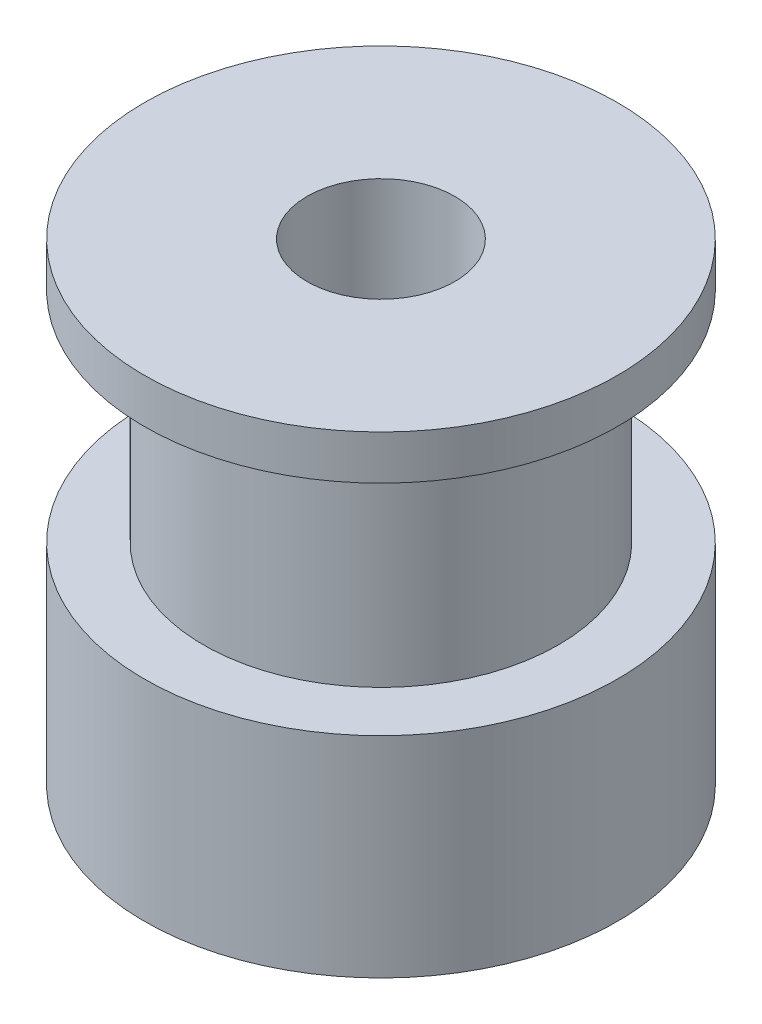
SolidWorks part; units mm, degrees
ref_plane "前视基准面" through (0, 0, 0) normal (0, 0, 1) x (1, 0, 0)
ref_plane "上视基准面" through (0, 0, 0) normal (0, 1, 0) x (1, 0, 0)
ref_plane "右视基准面" through (0, 0, 0) normal (1, 0, 0) x (0, 0, -1)
sketch "草图1" plane through (0, 0, 0) normal (0, 0, 1) x (1, 0, 0)
  line L0 (0, 0) -> (8, 0)
  line L1 (8, 0) -> (8, 7.1)
  line L2 (8, 7.1) -> (6, 7.1)
  line L3 (6, 7.1) -> (6, 14.5)
  line L4 (6, 14.5) -> (8, 14.5)
  line L5 (8, 14.5) -> (8, 16)
  line L6 (8, 16) -> (0, 16)
  line L7 (0, 16) -> (0, 0)
  dimension "D1" = 8
  dimension "D2" = 7.1
  dimension "D3" = 16
  dimension "D4" = 7.4
  dimension "D5" = 6
revolve "旋转1" add sketch "草图1" angle 360 about L7
sketch "草图2" plane through (0, 16, 0) normal (0, 1, 0) x (1, 0, 0)
  circle A0 centre (0, 0) radius 2.5
  dimension "D1" = 5
extrude "切除-拉伸1" cut sketch "草图2" against normal up to next
